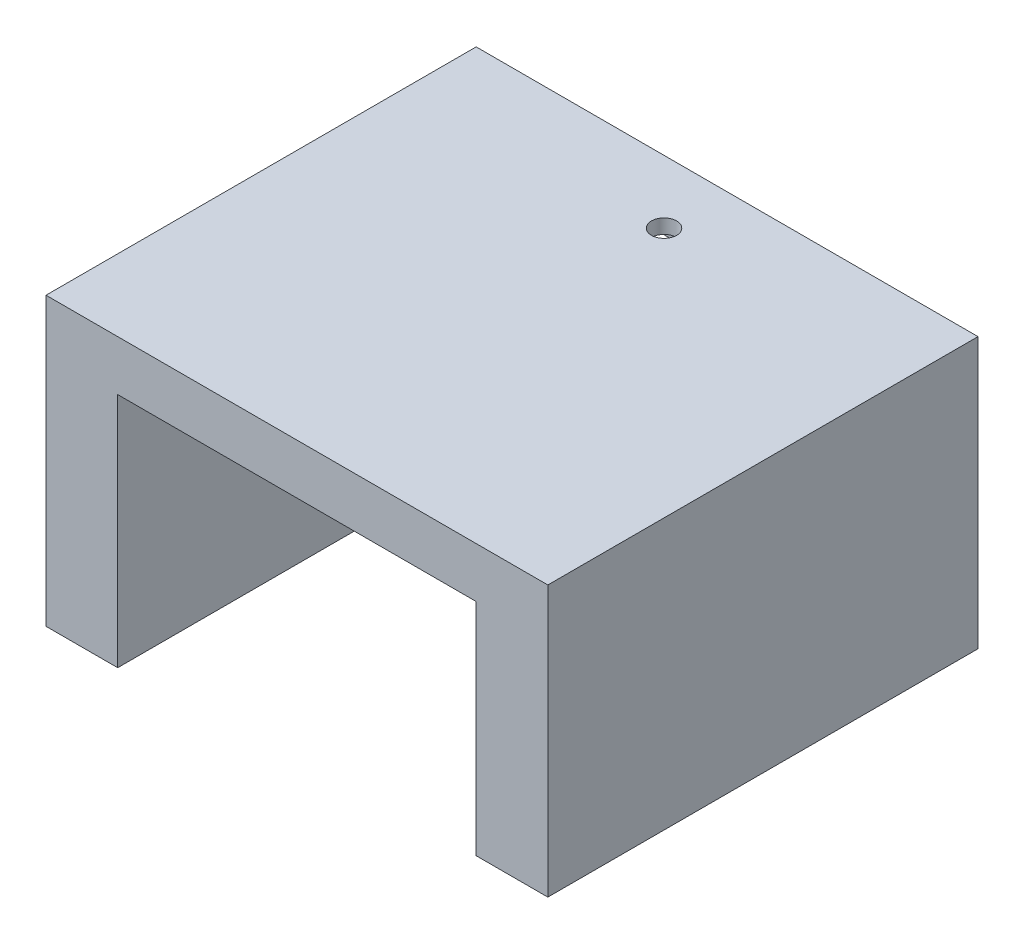
SolidWorks part; units mm, degrees
ref_plane "Front Plane" through (0, 0, 0) normal (0, 0, 1) x (1, 0, 0)
ref_plane "Top Plane" through (0, 0, 0) normal (0, 1, 0) x (1, 0, 0)
ref_plane "Right Plane" through (0, 0, 0) normal (1, 0, 0) x (0, 0, -1)
sketch "Sketch1" plane through (0, 0, 0) normal (0, 0, 1) x (1, 0, 0)
  line L2 (-58.9095, -8.3228) -> (-58.9095, -48.3228)
  line L4 (11.0905, -8.3228) -> (11.0905, -46.0338)
  line L10 (-48.9095, -15.3228) -> (-48.9095, -48.3228)
  line L11 (-48.9095, -15.3228) -> (1.0905, -15.3228)
  line L12 (1.0905, -15.3228) -> (1.0905, -46.0338)
  line L13 (-48.9095, -48.3228) -> (-58.9095, -48.3228)
  line L14 (1.0905, -46.0338) -> (11.0905, -46.0338)
  line L15 (11.0905, -8.3228) -> (-58.9095, -8.3228)
  point P4 (-53.9095, -48.3228)
  dimension "D1" = 70
  dimension "D2" = 40
  dimension "D3" = 10
  dimension "D4" = 10
  dimension "D5" = 7
extrude "Boss-Extrude1" add sketch "Sketch1" along normal blind 60
sketch "Sketch2" plane through (0, -15.3228, 0) normal (0, 1, 0) x (1, 0, 0)
  line L0 (-23.9095, 0) -> (-23.9095, -60) construction
  line L1 (-48.9095, 0) -> (1.0905, 0) construction
  line L2 (-23.9095, -60) -> (-33.849, -51.7842) construction
  line L3 (11.0905, -60) -> (-58.9095, -60) construction
  circle A0 centre (-23.9095, -8.7928) radius 1.75
  point P6 (0, 0)
  point P8 (-33.9095, -60)
  dimension "D1" = 3.5
extrude "Cut-Extrude1" cut sketch "Sketch2" against normal through all both and the other way through all from surface at 0 starting at face at (-23.9095, -15.3228, 30)
sketch "Sketch3" plane through (0, -15.3228, 0) normal (0, -1, 0) x (-1, 0, 0)
  line L0 (23.9095, 0) -> (23.9095, -14.99) construction
  line L5 (22.1595, -8.7928) -> (31.2992, -8.7928) construction
  line L7 (31.2992, -2.5956) -> (16.5199, -2.5956)
  line L8 (31.2992, -2.5956) -> (31.2992, -14.99)
  line L9 (31.2992, -14.99) -> (16.5199, -14.99)
  line L10 (16.5199, -2.5956) -> (16.5199, -14.99)
  line L11 (48.9095, 0) -> (-1.0905, 0) construction
  circle A0 centre (23.9095, -8.7928) radius 1.75 construction
  point P12 (0, 0)
  point P13 (0, 0)
  point P14 (0, 0)
  point P15 (0, 0)
  point P16 (0, 0)
  point P17 (0, 0)
  point P20 (23.9095, 0)
  dimension "D1" = 12.3944
  dimension "D2" = 14.7793
extrude "Cut-Extrude2" cut sketch "Sketch3" against normal blind 5
